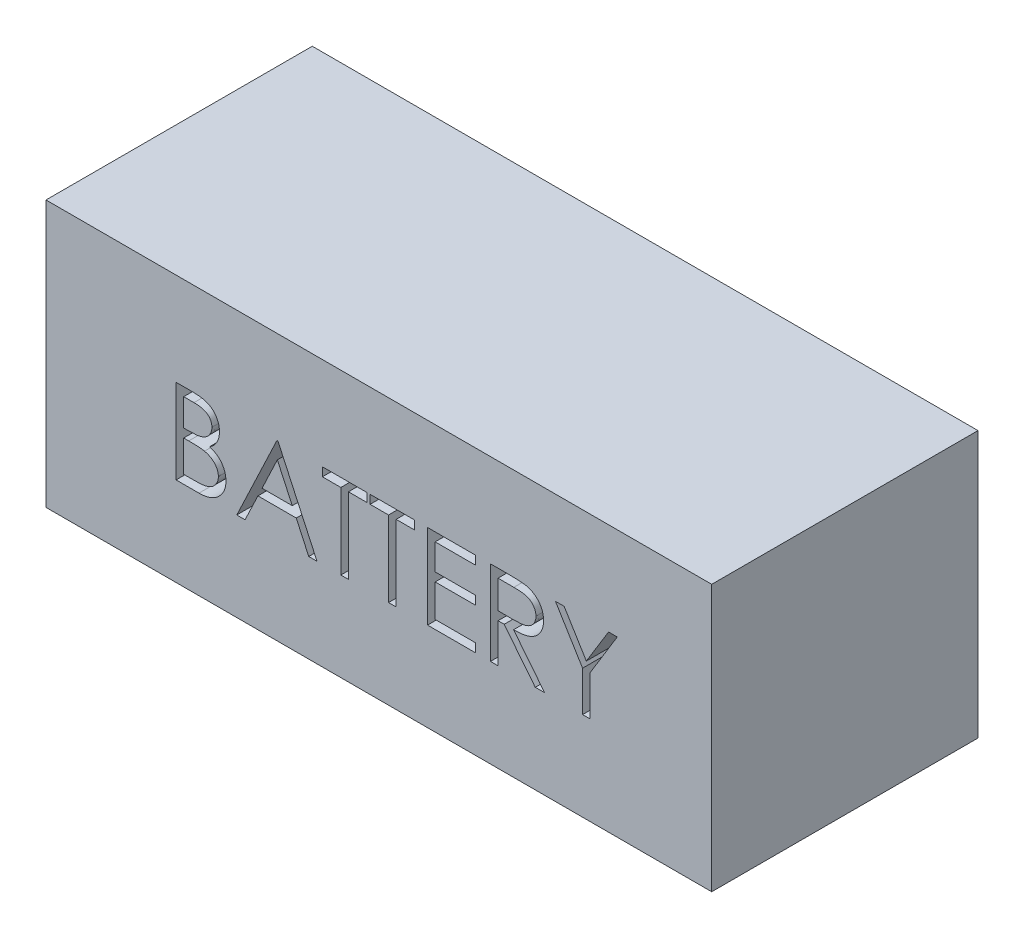
SolidWorks part; units mm, degrees
ref_plane "Front Plane" through (0, 0, 0) normal (0, 0, 1) x (1, 0, 0)
ref_plane "Top Plane" through (0, 0, 0) normal (0, 1, 0) x (1, 0, 0)
ref_plane "Right Plane" through (0, 0, 0) normal (1, 0, 0) x (0, 0, -1)
sketch "Sketch1" plane through (0, 0, 0) normal (1, 0, 0) x (0, 0, -1)
  line L1 (-30, 30) -> (30, 30)
  line L2 (-30, 30) -> (-30, -30)
  line L3 (-30, -30) -> (30, -30)
  line L4 (30, 30) -> (30, -30)
  point P4 (0, 30)
  point P5 (-30, 0)
  point P7 (0, 0)
  point P9 (0, 0)
  dimension "D1" = 60
  dimension "D2" = 60
extrude "Boss-Extrude1" add sketch "Sketch1" against normal mid plane 150 contours L2 L3 L4 L1
sketch "Sketch2" plane through (0, 0, 30) normal (0, 0, 1) x (1, 0, 0)
  text T0 "BATTERY" font "Century Gothic" height in points 72
  point P1 (-43.8045, -9.9746)
  point P2 (-48.1291, -9.9746)
extrude "Cut-Extrude1" cut sketch "Sketch2" against normal blind 10
